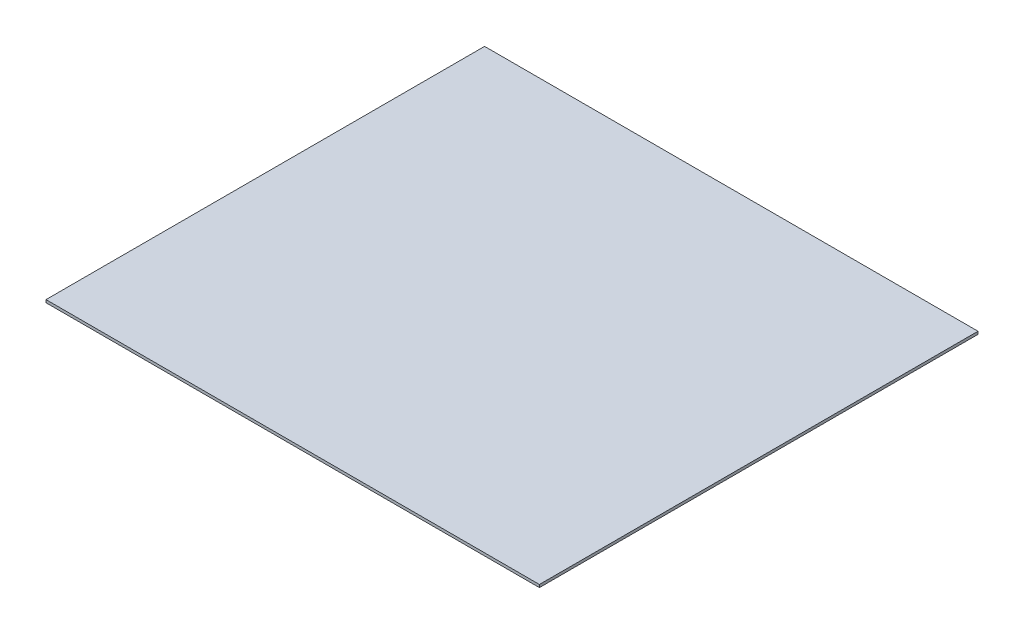
SolidWorks part; units mm, degrees
ref_plane "Front Plane" through (0, 0, 0) normal (0, 0, 1) x (1, 0, 0)
ref_plane "Top Plane" through (0, 0, 0) normal (0, 1, 0) x (1, 0, 0)
ref_plane "Right Plane" through (0, 0, 0) normal (1, 0, 0) x (0, 0, -1)
sketch "Sketch1" plane through (0, 0, 0) normal (0, 1, 0) x (1, 0, 0)
  line L1 (90, -80) -> (-90, -80)
  line L2 (90, -80) -> (90, 80)
  line L3 (90, 80) -> (-90, 80)
  line L4 (-90, -80) -> (-90, 80)
  line L5 (90, -80) -> (-90, 80) construction
  line L6 (90, 80) -> (-90, -80) construction
  point P0 (0, 0)
  dimension "D1" = 180
  dimension "D2" = 160
extrude "Boss-Extrude1" add sketch "Sketch1" along normal blind 1
sketch "Sketch2" plane through (0, 1, 0) normal (0, 1, 0) x (1, 0, 0)
  text T0 "MotherBoard" font "Century Gothic" height in points 48
